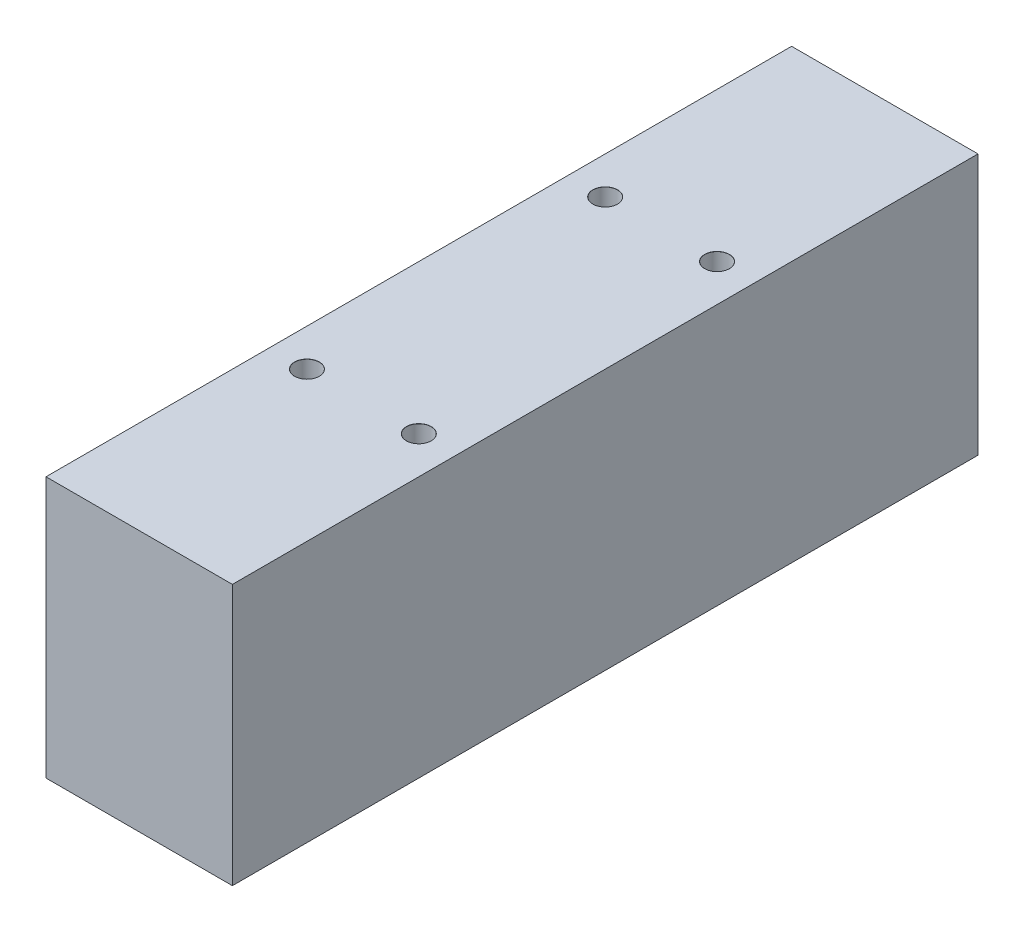
SolidWorks part; units mm, degrees
ref_plane "Front Plane" through (0, 0, 0) normal (0, 0, 1) x (1, 0, 0)
ref_plane "Top Plane" through (0, 0, 0) normal (0, 1, 0) x (1, 0, 0)
ref_plane "Right Plane" through (0, 0, 0) normal (1, 0, 0) x (0, 0, -1)
sketch "Sketch1" plane through (0, 0, 0) normal (0, 1, 0) x (1, 0, 0)
  line L1 (-25, 100) -> (25, 100)
  line L2 (-25, 100) -> (-25, -100)
  line L3 (-25, -100) -> (25, -100)
  line L4 (25, 100) -> (25, -100)
  line L5 (-25, 100) -> (25, -100) construction
  line L6 (-25, -100) -> (25, 100) construction
  point P0 (0, 0)
  dimension "D1" = 200
  dimension "D2" = 50
extrude "Boss-Extrude1" add sketch "Sketch1" along normal blind 70
hole_wizard "M6 Clearance Hole1" positions "Sketch2" profile "Sketch4" hole size "M6" standard "ANSI Metric"
sketch "Sketch2" plane through (0, 0, 0) normal (0, -1, 0) x (-1, 0, 0)
  line L0 (0, 75) -> (0, -75) construction
  point P0 (0, 75)
  point P2 (0, 0)
  point P5 (0, -75)
  point P12 (0, 0)
  dimension "D1" = 150
sketch "Sketch4" plane through (0, 0, -75) normal (1, 0, 0) x (0, 0, -1)
  line L0 (0, 0) -> (0, 5)
  line L1 (0, 5) -> (3.3, 3.0172)
  line L2 (3.3, 3.0172) -> (3.3, 0.021)
  line L3 (3.3, 0.021) -> (3.325, 0)
  line L5 (3.325, 0) -> (0, 0)
  line L6 (-3.3, 0.021) -> (-3.325, 0) construction
  line L10 (0, 5) -> (-3.3, 3.0172) construction
  line L11 (0, -6.35) -> (0, 107.95) construction
  dimension "Hole Dia." = 6.6
  dimension "Hole Depth" = 5
  dimension "Near C'Sink Dia." = 6.65
  dimension "Near C'Sink Angle" = 100
  dimension "Drill Angle" = 118
sketch "Sketch5" plane through (-25, 0, 0) normal (-1, 0, 0) x (0, 0, 1)
  line L0 (-60, 40) -> (60, 40) construction
  line L2 (-100, 70) -> (100, 70) construction
  circle A0 centre (-60, 40) radius 10
  circle A1 centre (60, 40) radius 10
  circle A2 centre (0, 40) radius 18.5
  point P6 (0, 40)
  dimension "D1" = 20
  dimension "D3" = 37
  dimension "D2" = 120
  dimension "D4" = 30
extrude "Cut-Extrude1" cut sketch "Sketch5" against normal offset from surface (40 mm away) 10 up to face at (25, 35, 0)
hole_wizard "M6 Clearance Hole2" positions "Sketch8" profile "Sketch9" hole size "M6" standard "ANSI Metric" end condition up to next
sketch "Sketch8" plane through (0, 70, 0) normal (0, 1, 0) x (1, 0, 0)
  line L0 (-15, 40) -> (15, 40) construction
  line L1 (15, 40) -> (15, -40) construction
  line L3 (25, -100) -> (25, 100) construction
  point P0 (-15, 40)
  point P2 (15, 40)
  point P4 (-15, -40)
  point P6 (15, -40)
  point P13 (0, 0)
  point P14 (0, 0)
  point P15 (15, 0)
  point P17 (0, 40)
  dimension "D1" = 10
  dimension "D2" = 80
sketch "Sketch9" plane through (-15, 70, -40) normal (1, 0, 0) x (0, 0, 1)
  line L0 (0, 0) -> (0, 70)
  line L1 (0, 70) -> (3.3, 70)
  line L2 (3.3, 70) -> (3.3, 0.021)
  line L3 (3.3, 0.021) -> (3.325, 0)
  line L5 (3.325, 0) -> (0, 0)
  line L6 (-3.3, 0.021) -> (-3.325, 0) construction
  line L11 (0, -6.35) -> (0, 107.95) construction
  dimension "Thru Hole Dia." = 6.6
  dimension "Thru Hole Depth" = 70
  dimension "Near C'Sink Dia." = 6.65
  dimension "Near C'Sink Angle" = 100
